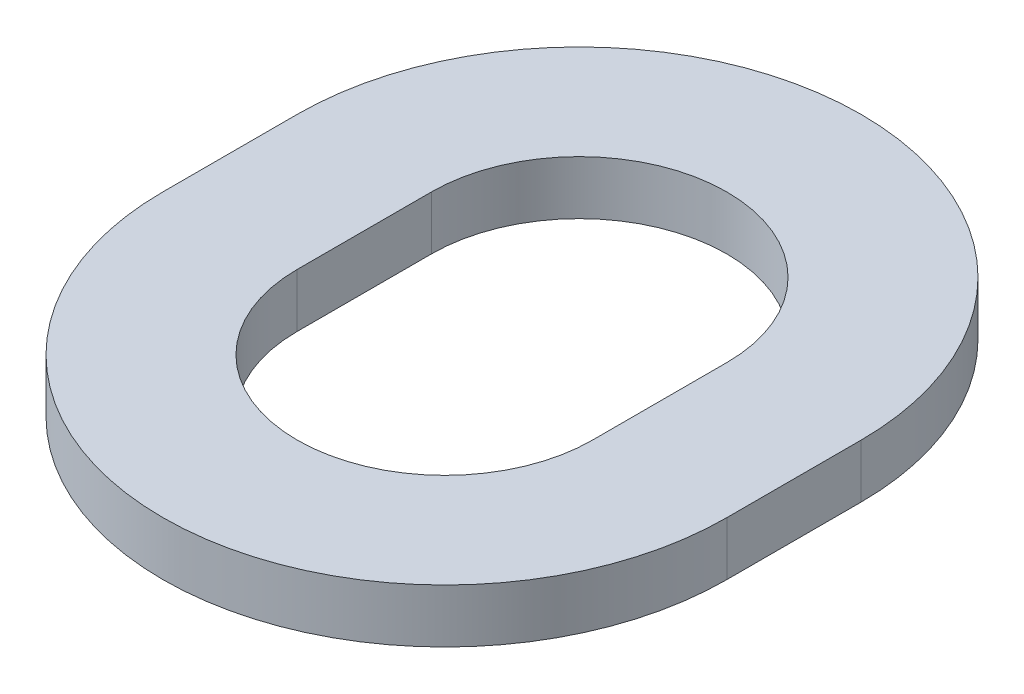
SolidWorks part; units mm, degrees
ref_plane "前视基准面" through (0, 0, 0) normal (0, 0, 1) x (1, 0, 0)
ref_plane "上视基准面" through (0, 0, 0) normal (0, 1, 0) x (1, 0, 0)
ref_plane "右视基准面" through (0, 0, 0) normal (1, 0, 0) x (0, 0, -1)
sketch "草图1" plane through (0, 0, 0) normal (0, 1, 0) x (1, 0, 0)
  line L0 (11, 0) -> (11, -10)
  line L1 (-11, 0) -> (-11, -10)
  line L2 (-21, 0) -> (-21, -10)
  line L3 (21, 0) -> (21, -10)
  arc A0 (11, 0) -> (-11, 0) centre (0, 0) ccw
  arc A1 (11, -10) -> (-11, -10) centre (0, -10) cw
  arc A2 (21, 0) -> (-21, 0) centre (0, 0) ccw
  arc A3 (21, -10) -> (-21, -10) centre (0, -10) cw
  dimension "D1" = 11
  dimension "D2" = 10
  dimension "D3" = 10
extrude "凸台-拉伸2" add sketch "草图1" along normal blind 4
